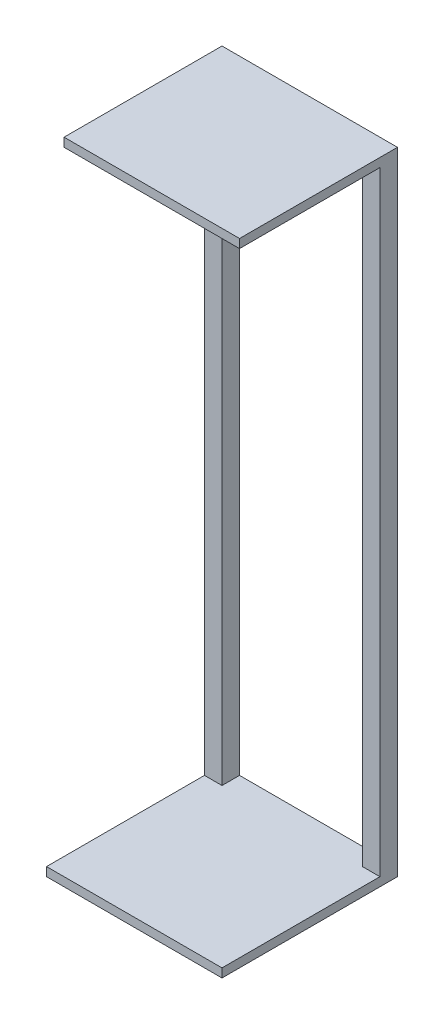
SolidWorks part; units mm, degrees
ref_plane "Front Plane" through (0, 0, 0) normal (0, 0, 1) x (1, 0, 0)
ref_plane "Top Plane" through (0, 0, 0) normal (0, 1, 0) x (1, 0, 0)
ref_plane "Right Plane" through (0, 0, 0) normal (1, 0, 0) x (0, 0, -1)
sketch "Sketch2" plane through (0, 0, 0) normal (0, 1, 0) x (1, 0, 0)
  line L1 (0, 0) -> (200, 0)
  line L2 (0, 0) -> (0, 200)
  line L3 (0, 200) -> (200, 200)
  line L4 (200, 0) -> (200, 200)
  dimension "D1" = 200
  dimension "D2" = 200
extrude "Boss-Extrude1" add sketch "Sketch2" along normal blind 10
sketch "Sketch3" plane through (0, 10, 0) normal (0, 1, 0) x (1, 0, 0)
  line L0 (0, -55) -> (0, 55) construction
  line L1 (200, 200) -> (180, 200)
  line L2 (200, 200) -> (200, 180)
  line L3 (200, 180) -> (180, 180)
  line L4 (180, 200) -> (180, 180)
  line L5 (200, 200) -> (0, 200) construction
  line L7 (0, 200) -> (20, 200)
  line L8 (0, 200) -> (0, 180)
  line L9 (0, 180) -> (20, 180)
  line L10 (20, 200) -> (20, 180)
  point P5 (0, 200)
  dimension "D1" = 20
  dimension "D2" = 20
  dimension "D3" = 20
  dimension "D4" = 20
extrude "Boss-Extrude2" add sketch "Sketch3" along normal blind 700
sketch "Sketch4" plane through (0, 710, 0) normal (0, 1, 0) x (1, 0, 0)
  line L0 (0, -110) -> (0, 110) construction
  line L1 (200, 200) -> (0, 200)
  line L2 (200, 200) -> (200, 20)
  line L3 (200, 20) -> (0, 20)
  line L4 (0, 200) -> (0, 20)
  dimension "D1" = 180
extrude "Boss-Extrude3" add sketch "Sketch4" along normal blind 10
sketch "Sketch5" plane through (0, 710, 0) normal (0, -1, 0) x (1, 0, 0)
  line L0 (100, -20) -> (100, -200) construction
  line L1 (0, -20) -> (200, -20) construction
  line L2 (180, -200) -> (20, -200) construction
  line L3 (0, -110) -> (200, -110)
  line L4 (200, -20) -> (200, -180) construction
  line L5 (0, -100) -> (200, -100) construction
  line L6 (0, -180) -> (0, -20) construction
  line L8 (80, -100) -> (120, -100)
  line L9 (80, -100) -> (80, -120)
  line L10 (80, -120) -> (120, -120)
  line L11 (120, -100) -> (120, -120)
  line L12 (80, -100) -> (120, -120) construction
  line L13 (80, -120) -> (120, -100) construction
  point P11 (100, -110)
  point P15 (100, -110)
  dimension "D1" = 40
  dimension "D2" = 20
extrude "Boss-Extrude4" add sketch "Sketch5" along normal blind 20 contours L11 L8 L9 L3 | L11 L3 L9 L10
sketch "Sketch7" plane through (120, 0, 0) normal (1, 0, 0) x (0, 0, -1)
  line L0 (110, 690) -> (110, 710) construction
  line L1 (100, 690) -> (120, 690) construction
  line L2 (20, 710) -> (180, 710) construction
  circle A0 centre (110, 690) radius 10
extrude "Boss-Extrude7" add sketch "Sketch7" against normal up to surface (40 mm away) contours A0 up to face at (80, 700, -110)
sketch "Sketch10" plane through (0, 0, -100) normal (0, 0, 1) x (1, 0, 0)
  line L0 (80, 710) -> (120, 710) construction
  line L1 (85, 710) -> (115, 710)
  line L2 (85, 710) -> (85, 669.7183)
  line L3 (85, 669.7183) -> (115, 669.7183)
  line L4 (115, 710) -> (115, 669.7183)
  line L5 (80, 690) -> (80, 710) construction
  line L6 (120, 690) -> (120, 710) construction
  dimension "D1" = 5
  dimension "D2" = 5
extrude "Cut-Extrude2" cut sketch "Sketch10" against normal through all
sketch "Sketch11" plane through (120, 0, 0) normal (1, 0, 0) x (0, 0, -1)
  line L0 (100, 690) -> (120, 690) construction
  circle A0 centre (110, 690) radius 5
extrude "Boss-Extrude9" add sketch "Sketch11" against normal up to surface (40 mm away) up to face at (80, 697.5, -110)
pattern_linear "LPattern1" count 2 spacing 80 along (0, 0, -1) of "Boss-Extrude7", "Cut-Extrude2", "Boss-Extrude9", "Boss-Extrude4"
